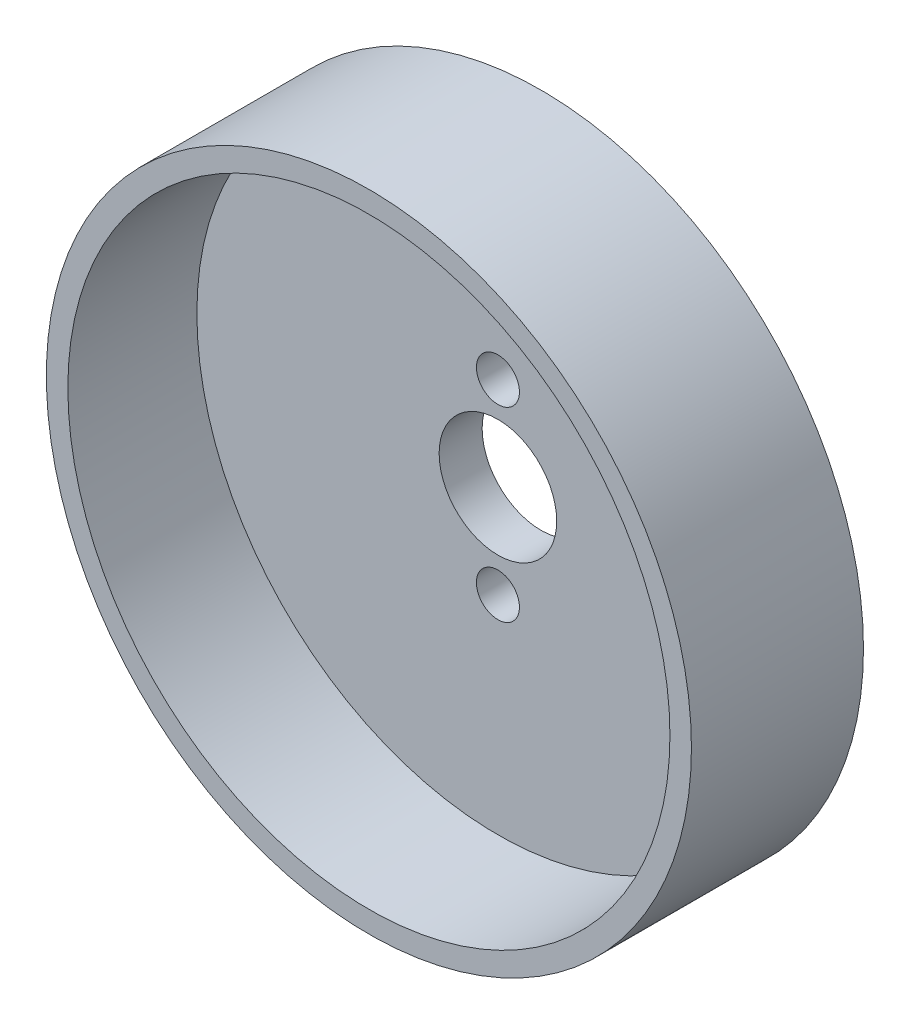
SolidWorks part; units mm, degrees
material "1060 合金"
ref_plane "前视基准面" through (0, 0, 0) normal (0, 0, 1) x (1, 0, 0)
ref_plane "上视基准面" through (0, 0, 0) normal (0, 1, 0) x (1, 0, 0)
ref_plane "右视基准面" through (0, 0, 0) normal (1, 0, 0) x (0, 0, -1)
sketch "草图1" plane through (0, 0, 0) normal (0, 0, 1) x (1, 0, 0)
  circle A1 centre (0, 0) radius 22.5
  dimension "D1" = 45
extrude "凸台-拉伸1" add sketch "草图1" along normal blind 3
sketch "草图2" plane through (0, 0, 3) normal (0, 0, 1) x (1, 0, 0)
  circle A0 centre (0, 0) radius 21
  circle A2 centre (0, 0) radius 22.5
  circle A3 centre (0, 0) radius 22.5
  dimension "D2" = 42
  dimension "D1" = 0
extrude "凸台-拉伸2" add sketch "草图2" along normal blind 9
sketch "草图4" plane through (0, 0, 0) normal (0, 0, -1) x (-1, 0, 0)
  circle A0 centre (0, 0) radius 4.1
  circle A1 centre (0, 0) radius 6.5 construction
  circle A2 centre (0, 6.5) radius 1.5
  circle A3 centre (0, -6.5) radius 1.5
  dimension "D1" = 8.2
  dimension "D2" = 13
  dimension "D3" = 3
extrude "切除-拉伸1" cut sketch "草图4" against normal through all
